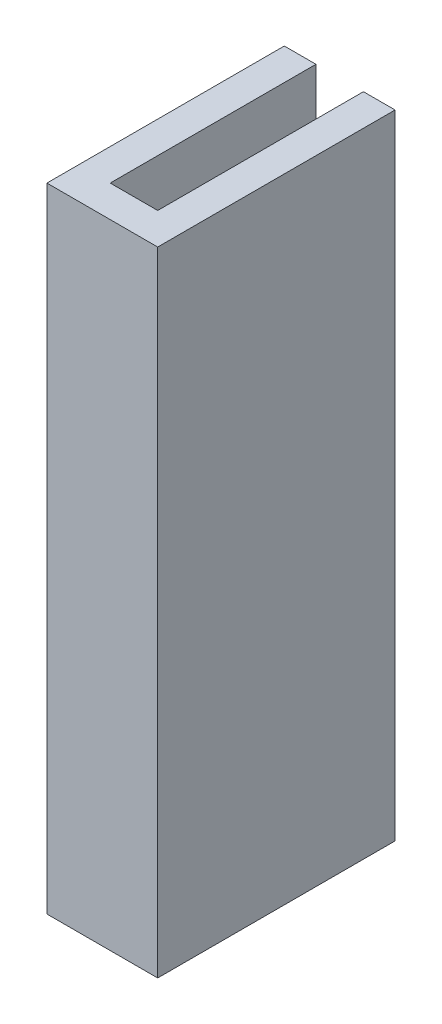
SolidWorks part; units mm, degrees
ref_plane "Front Plane" through (0, 0, 0) normal (0, 0, 1) x (1, 0, 0)
ref_plane "Top Plane" through (0, 0, 0) normal (0, 1, 0) x (1, 0, 0)
ref_plane "Right Plane" through (0, 0, 0) normal (1, 0, 0) x (0, 0, -1)
sketch "Sketch1" plane through (0, 0, 0) normal (0, 1, 0) x (1, 0, 0)
  line L0 (-3.5, 15) -> (-3.5, 0)
  line L1 (-3.5, 0) -> (3.5, 0)
  line L2 (3.5, 0) -> (3.5, 15)
  line L3 (3.5, 15) -> (1.5, 15)
  line L4 (1.5, 15) -> (1.5, 2)
  line L5 (1.5, 2) -> (-1.5, 2)
  line L6 (-1.5, 2) -> (-1.5, 15)
  line L7 (-1.5, 15) -> (-3.5, 15)
  point P6 (0, 0)
  dimension "D1" = 3
  dimension "D2" = 2
  dimension "D3" = 15
  dimension "D4" = 2
extrude "Boss-Extrude1" add sketch "Sketch1" along normal blind 40
sketch "Sketch3" plane through (0, 0, -15) normal (0, 0, -1) x (-1, 0, 0)
  line L0 (3.5, 40) -> (3.5, 0) construction
  line L1 (-2.5, 31.5) -> (2.5, 31.5)
  line L2 (-2.5, 31.5) -> (-2.5, 8.5)
  line L3 (-2.5, 8.5) -> (2.5, 8.5)
  line L4 (2.5, 31.5) -> (2.5, 8.5)
  line L5 (-3.5, 40) -> (-3.5, 0) construction
  point P4 (2.5, 20)
  point P7 (3.5, 20)
  point P8 (0, 8.5)
  dimension "D1" = 23
  dimension "D2" = 1
extrude "Cut-Extrude1" cut sketch "Sketch3" against normal up to surface (13 mm away) up to face at (0, 20, -2)
